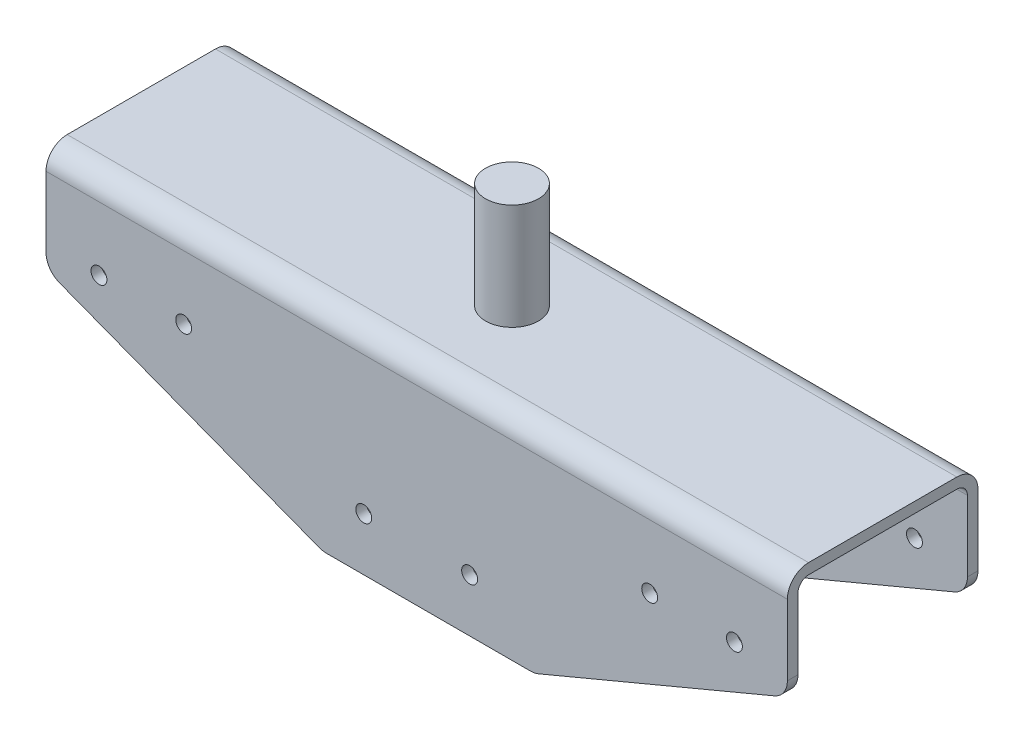
SolidWorks part; units mm, degrees
ref_plane "Front Plane" through (0, 0, 0) normal (0, 0, 1) x (1, 0, 0)
ref_plane "Top Plane" through (0, 0, 0) normal (0, 1, 0) x (1, 0, 0)
ref_plane "Right Plane" through (0, 0, 0) normal (1, 0, 0) x (0, 0, -1)
sketch "Sketch1" plane through (0, 0, 0) normal (0, 0, 1) x (1, 0, 0)
  line L1 (-8.4984, -10) -> (10.73, -10)
  line L2 (-35, 1.3761) -> (-35, 10)
  line L3 (-35, 10) -> (35, 10)
  line L4 (35, 1.3305) -> (35, 10)
  line L5 (-20.0386, -5.7253) -> (35, 10) construction
  line L6 (-35, 10) -> (20.8093, -5.9455) construction
  line L8 (-33.7148, -0.4918) -> (-9.2132, -9.8679)
  line L9 (-8.868, -10) -> (11.132, -10)
  line L10 (11.5028, -9.8446) -> (33.7729, -0.5141)
  arc A0 (35, 1.3305) -> (33.7729, -0.5141) centre (33, 1.3305) cw
  arc A1 (11.5028, -9.8446) -> (10.73, -10) centre (10.73, -8) cw
  arc A2 (-8.4984, -10) -> (-9.2132, -9.8679) centre (-8.4984, -8) cw
  arc A3 (-33.7148, -0.4918) -> (-35, 1.3761) centre (-33, 1.3761) cw
  point P0 (0, 0)
  point P11 (35, 0)
  point P21 (-35, 0)
  dimension "D6" = 2
  dimension "D1" = 70
  dimension "D2" = 10
  dimension "D3" = 20
  dimension "D4" = 10
  dimension "D5" = 20
extrude "Boss-Extrude1" add sketch "Sketch1" along normal mid plane 18 contours A3 L8 A2 L1 A1 L10 A0 L4 L3 L2
fillet "Fillet1" radius 2 2 edges at (0, 10, -9) (0, 10, 9)
sketch "Sketch2" plane through (0, 0, 0) normal (1, 0, 0) x (0, 0, -1)
  line L9 (-8, 8) -> (-8, -14.2343)
  line L10 (-8, -14.2343) -> (8, -14.2343)
  line L11 (8, 8) -> (8, 1.3305)
  line L12 (-7, 9) -> (7, 9)
  line L13 (8, 8) -> (8, 1.3305)
  line L14 (-7, 9) -> (7, 9)
  line L15 (8, -14.2343) -> (8, 1.3305)
  arc A2 (-7, 9) -> (-8, 8) centre (-7, 8) ccw
  arc A3 (-7, 9) -> (-8, 8) centre (-7, 8) ccw
  arc A8 (8, 8) -> (7, 9) centre (7, 8) ccw
  arc A9 (8, 8) -> (7, 9) centre (7, 8) ccw
  dimension "D1" = 1
  dimension "D2" = 1
extrude "Cut-Extrude1" cut sketch "Sketch2" against normal through all both and the other way through all
sketch "Sketch3" plane through (0, 10, 0) normal (0, 1, 0) x (1, 0, 0)
  circle A0 centre (0, 0) radius 2.5
  dimension "D1" = 5
extrude "Boss-Extrude2" add sketch "Sketch3" along normal blind 10
sketch "Sketch4" plane through (0, 0, 0) normal (0, 0, 1) x (1, 0, 0)
  line L0 (0, 0) -> (0, -18.6662) construction
  line L1 (-35, 10) -> (35, 10) construction
  line L2 (-8.4984, -10) -> (10.73, -10) construction
  line L3 (-35, 1.3761) -> (-35, 8) construction
  circle A0 centre (-30, 2) radius 0.75
  circle A1 centre (-22, 2) radius 0.75
  circle A4 centre (-5, -5) radius 0.75
  circle A5 centre (5, -5) radius 0.75
  circle A6 centre (22, 2) radius 0.75
  circle A7 centre (30, 2) radius 0.75
  dimension "D1" = 1.5
  dimension "D2" = 1.5
  dimension "D5" = 1.5
  dimension "D3" = 8
  dimension "D4" = 8
  dimension "D6" = 5
  dimension "D7" = 5
  dimension "D8" = 5
extrude "Cut-Extrude2" cut sketch "Sketch4" against normal through all both and the other way through all
equation "\"1。5\"=2"
